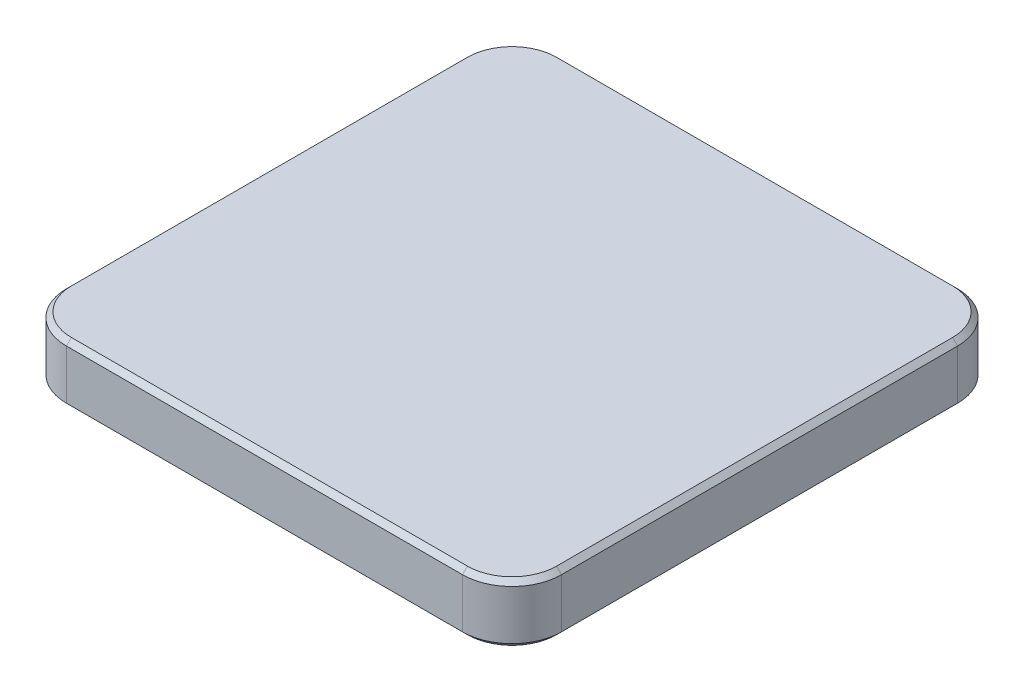
SolidWorks part; units mm, degrees
ref_plane "Front Plane" through (0, 0, 0) normal (0, 0, 1) x (1, 0, 0)
ref_plane "Top Plane" through (0, 0, 0) normal (0, 1, 0) x (1, 0, 0)
ref_plane "Right Plane" through (0, 0, 0) normal (1, 0, 0) x (0, 0, -1)
sketch "Sketch1" plane through (0, 0, 0) normal (0, 1, 0) x (1, 0, 0)
  line L0 (-40, 50) -> (40, 50)
  line L1 (50, 40) -> (50, -40)
  line L2 (40, -50) -> (-40, -50)
  line L3 (-50, -40) -> (-50, 40)
  arc A0 (-40, -50) -> (-50, -40) centre (-40, -40) cw
  arc A1 (50, -40) -> (40, -50) centre (40, -40) cw
  arc A2 (40, 50) -> (50, 40) centre (40, 40) cw
  arc A3 (-40, 50) -> (-50, 40) centre (-40, 40) ccw
  point P3 (0, 50)
  point P5 (-50, 0)
  dimension "D1" = 10
  dimension "D2" = 100
extrude "Boss-Extrude1" add sketch "Sketch1" along normal blind 12
chamfer "Chamfer1" distance 1 angle 45 16 edges at (-50, 0, 0) (-47.0711, 0, 47.0711) (-47.0711, 0, -47.0711) (0, 0, 50) (0, 0, -50) (47.0711, 0, 47.0711) (47.0711, 0, -47.0711) (50, 0, 0) (0, 12, -50) (-47.0711, 12, -47.0711) (47.0711, 12, -47.0711) (-50, 12, 0) (50, 12, 0) (-47.0711, 12, 47.0711) (47.0711, 12, 47.0711) (0, 12, 50)
